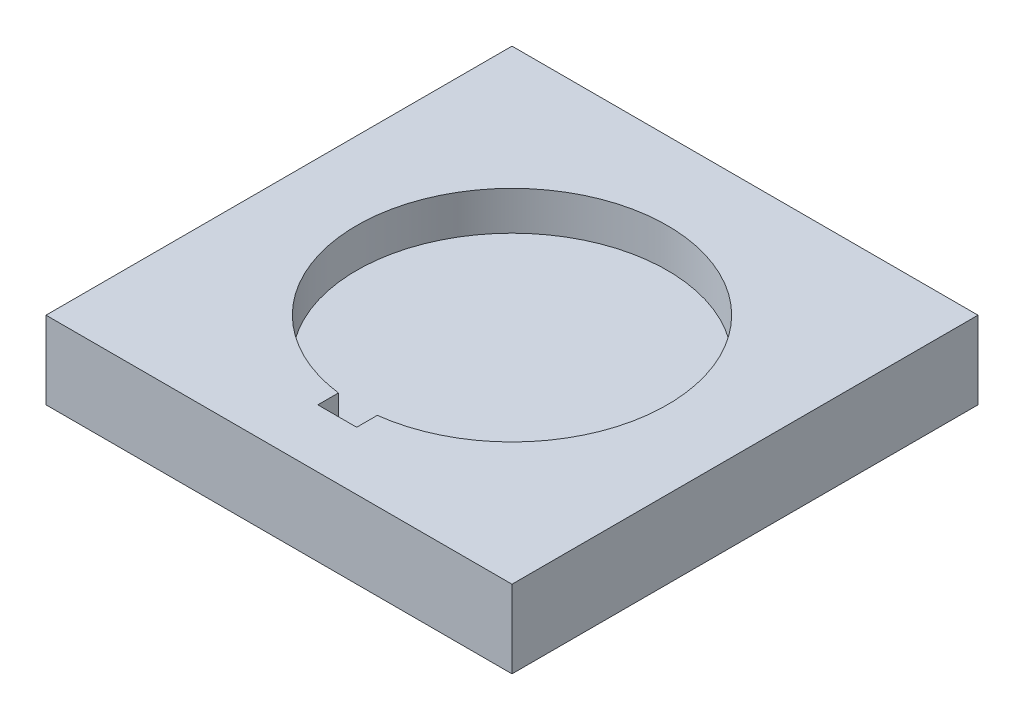
SolidWorks part; units mm, degrees
ref_plane "Front Plane" through (0, 0, 0) normal (0, 0, 1) x (1, 0, 0)
ref_plane "Top Plane" through (0, 0, 0) normal (0, 1, 0) x (1, 0, 0)
ref_plane "Right Plane" through (0, 0, 0) normal (1, 0, 0) x (0, 0, -1)
sketch "Sketch1" plane through (0, 0, 0) normal (0, 1, 0) x (1, 0, 0)
  line L1 (-76.2, 76.2) -> (76.2, 76.2)
  line L2 (-76.2, 76.2) -> (-76.2, -76.2)
  line L3 (-76.2, -76.2) -> (76.2, -76.2)
  line L4 (76.2, 76.2) -> (76.2, -76.2)
  dimension "D1" = 152.4
  dimension "D2" = 152.4
  dimension "D3" = 76.2
  dimension "D4" = 76.2
extrude "Boss-Extrude1" add sketch "Sketch1" against normal blind 25.4
sketch "Sketch2" plane through (0, 0, 0) normal (0, 1, 0) x (1, 0, 0)
  line L0 (-1000, 0) -> (49000, 0) construction
  line L1 (0, -1000) -> (0, 49000) construction
  line L2 (-76.2, -76.2) -> (76.2, -76.2) construction
  line L4 (-6.35, -50.4016) -> (-6.35, -57.15)
  line L5 (-6.35, -57.15) -> (6.35, -57.15)
  line L6 (6.35, -50.4016) -> (6.35, -57.15)
  arc A0 (6.35, -50.4016) -> (-6.35, -50.4016) centre (0, 0) ccw
  dimension "D1" = 101.6
  dimension "D2" = 12.7
  dimension "D3" = 6.35
  dimension "D4" = 19.05
extrude "Cut-Extrude1" cut sketch "Sketch2" against normal blind 12.7
